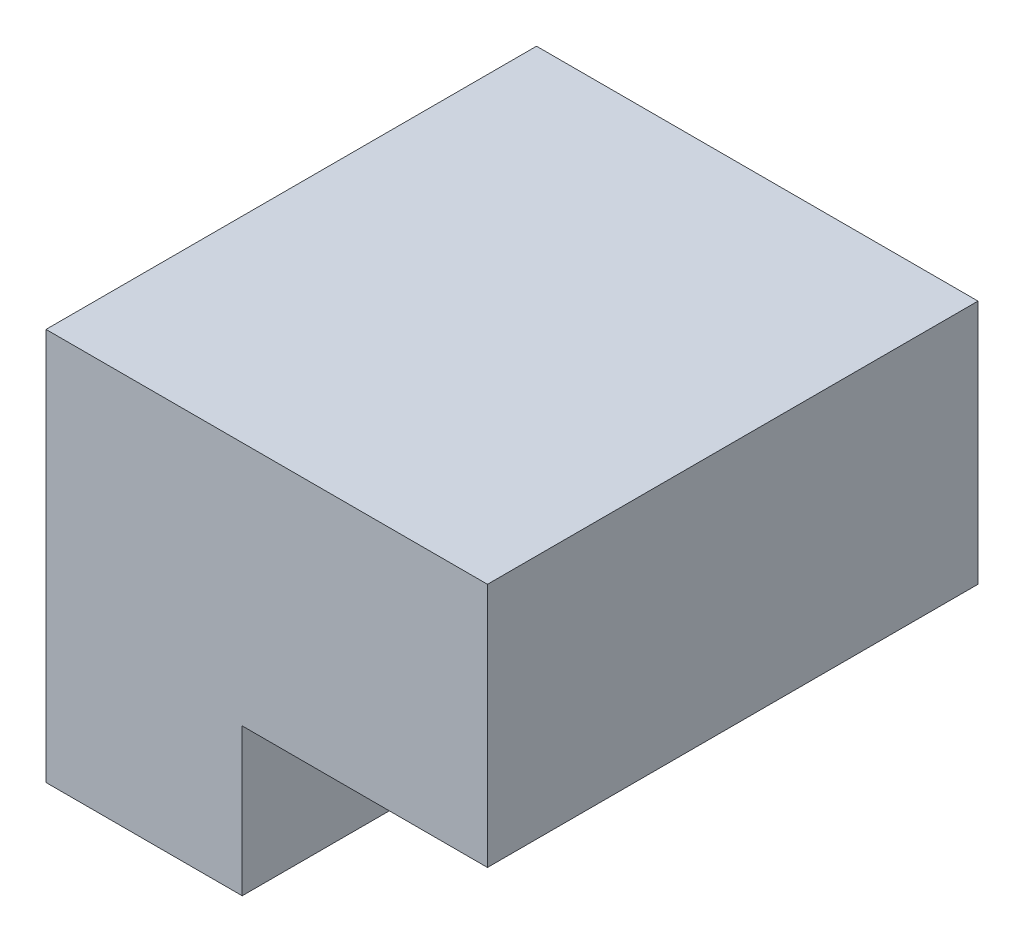
SolidWorks part; units mm, degrees
ref_plane "Front Plane" through (0, 0, 0) normal (0, 0, 1) x (1, 0, 0)
ref_plane "Top Plane" through (0, 0, 0) normal (0, 1, 0) x (1, 0, 0)
ref_plane "Right Plane" through (0, 0, 0) normal (1, 0, 0) x (0, 0, -1)
sketch "Sketch1" plane through (0, 0, 0) normal (0, 0, 1) x (1, 0, 0)
  line L0 (0, 0) -> (0, 8)
  line L1 (0, 8) -> (9, 8)
  line L2 (9, 8) -> (9, 3)
  line L3 (9, 3) -> (4, 3)
  line L4 (4, 3) -> (4, 0)
  line L5 (4, 0) -> (0, 0)
  dimension "D1" = 3
  dimension "D2" = 4
  dimension "D3" = 5
  dimension "D4" = 8
extrude "Boss-Extrude1" add sketch "Sketch1" along normal blind 10
